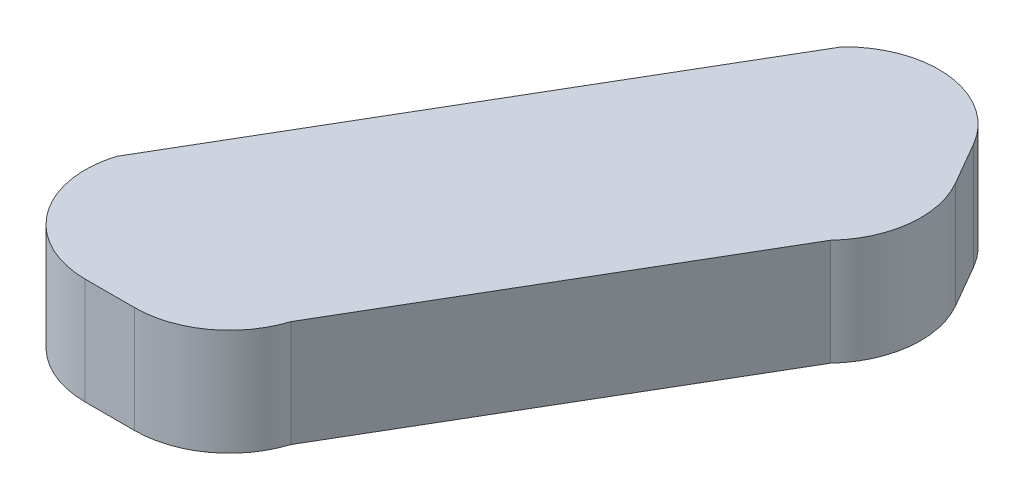
SolidWorks part; units mm, degrees
material "Oak"
ref_plane "Front Plane" through (0, 0, 0) normal (0, 0, 1) x (1, 0, 0)
ref_plane "Top Plane" through (0, 0, 0) normal (0, 1, 0) x (1, 0, 0)
ref_plane "Right Plane" through (0, 0, 0) normal (1, 0, 0) x (0, 0, -1)
sketch "Sketch1" plane through (0, 0, 0) normal (0, 1, 0) x (1, 0, 0)
  line L0 (0, -1498.1409) -> (0, 73408.9065) construction
  line L1 (-1498.1409, 0) -> (73408.9065, 0) construction
  line L9 (-500, 866.0254) -> (24500, -42435.2448) construction
  line L12 (-53.5836, 60.8095) -> (-55.6685, 64.4206)
  line L15 (-83.3307, 17) -> (-79.1454, 17)
  line L17 (-54.6793, 51.3339) -> (-71.517, 22.5904)
  line L18 (-68.3527, 65.9766) -> (-90.9933, 27.2989)
  circle A0 centre (0, 0) radius 90 construction
  arc A18 (-55.6685, 64.4206) -> (-68.3527, 65.9766) centre (-62.5967, 60.4206) ccw
  arc A24 (-53.5836, 60.8095) -> (-54.6793, 51.3339) centre (-60.5118, 56.8095) cw
  arc A25 (-71.517, 22.5904) -> (-79.1454, 17) centre (-79.1454, 25) cw
  arc A26 (-83.3307, 17) -> (-90.9933, 27.2989) centre (-83.3307, 25) cw
  point P10 (-60.6779, 73.0972)
  dimension "D1" = 180
  dimension "D7" = 33.3121
  dimension "D11" = 8
  dimension "D5" = 8
  dimension "D15" = 8
  dimension "D9" = 30
  dimension "D14" = 19.1851
  dimension "D16" = 50.7216
  dimension "D17" = 59.639
  dimension "D18" = 36.8654
extrude "Boss-Extrude1" add sketch "Sketch1" along normal mid plane 9
